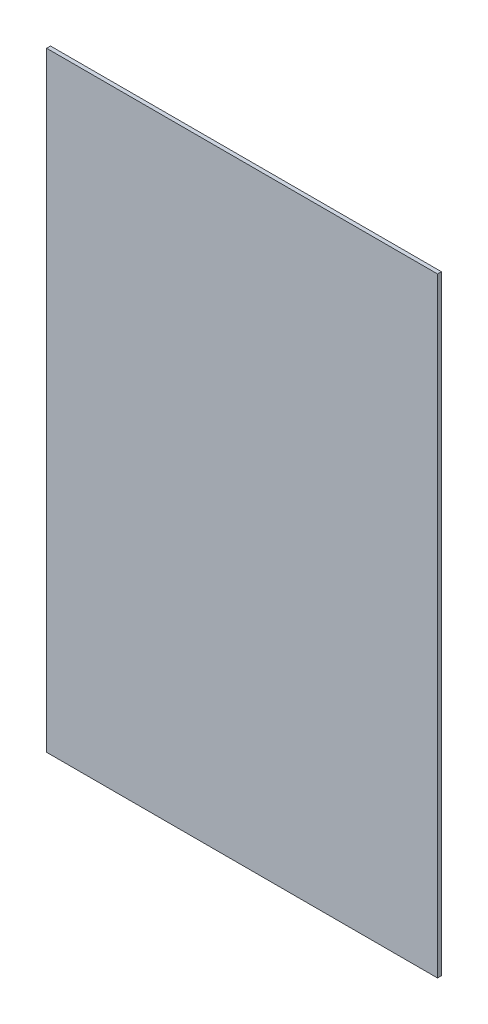
SolidWorks part; units mm, degrees
ref_plane "Front Plane" through (0, 0, 0) normal (0, 0, 1) x (1, 0, 0)
ref_plane "Top Plane" through (0, 0, 0) normal (0, 1, 0) x (1, 0, 0)
ref_plane "Right Plane" through (0, 0, 0) normal (1, 0, 0) x (0, 0, -1)
sketch "Sketch1" plane through (0, 0, 0) normal (0, 0, 1) x (1, 0, 0)
  line L1 (-635, -990.6) -> (635, -990.6)
  line L2 (-635, -990.6) -> (-635, 990.6)
  line L3 (-635, 990.6) -> (635, 990.6)
  line L4 (635, -990.6) -> (635, 990.6)
  line L5 (-635, -990.6) -> (635, 990.6) construction
  line L6 (-635, 990.6) -> (635, -990.6) construction
  point P0 (0, 0)
  dimension "D1" = 1981.2
  dimension "D2" = 1270
extrude "Boss-Extrude1" add sketch "Sketch1" along normal blind 12.7
